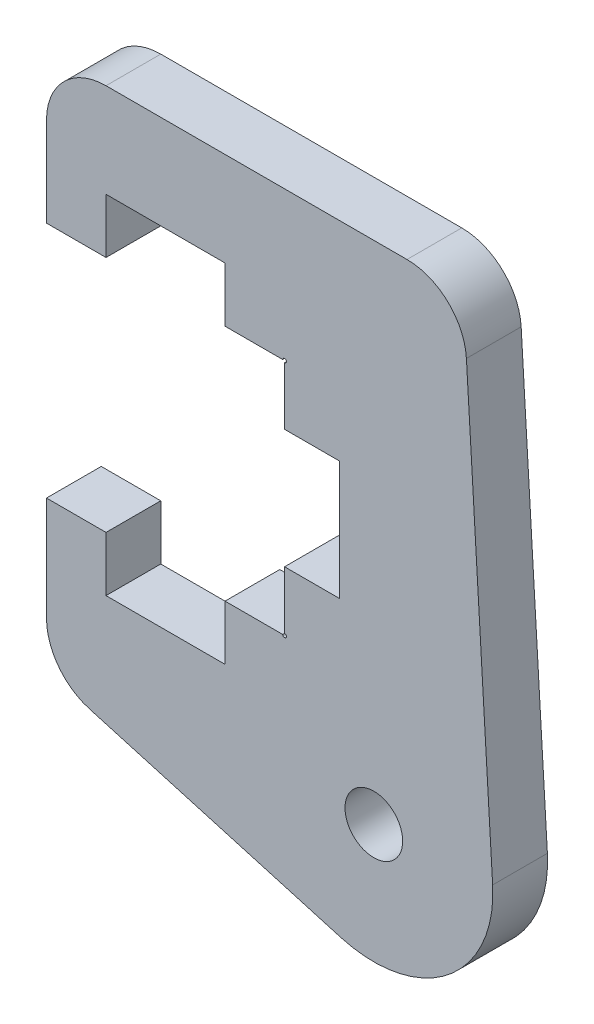
SolidWorks part; units mm, degrees
ref_plane "Front Plane" through (0, 0, 0) normal (0, 0, 1) x (1, 0, 0)
ref_plane "Top Plane" through (0, 0, 0) normal (0, 1, 0) x (1, 0, 0)
ref_plane "Right Plane" through (0, 0, 0) normal (1, 0, 0) x (0, 0, -1)
sketch "Sketch1" plane through (0, 0, 0) normal (0, 0, 1) x (1, 0, 0)
  line L0 (0, 12.7) -> (0, -12.7) construction
  line L1 (12.7, -12.7) -> (6.35, -12.7)
  line L2 (12.7, -12.7) -> (12.7, -6.35)
  line L3 (12.7, 12.7) -> (6.35, 12.7)
  line L4 (-12.7, 12.7) -> (-12.7, 28.575)
  line L5 (12.7, -12.7) -> (-12.7, 12.7) construction
  line L6 (12.7, 12.7) -> (-12.7, -12.7) construction
  line L7 (-12.7, 0) -> (12.7, 0) construction
  line L8 (12.7, 6.35) -> (12.7, 12.7)
  line L9 (18.542, -6.35) -> (12.7, -6.35)
  line L10 (18.542, -6.35) -> (18.542, 6.35)
  line L11 (18.542, 6.35) -> (12.7, 6.35)
  line L12 (-6.35, 12.7) -> (-12.7, 12.7)
  line L13 (18.542, -6.35) -> (12.7, 6.35) construction
  line L14 (18.542, 6.35) -> (12.7, -6.35) construction
  line L15 (6.35, 18.542) -> (-6.35, 18.542)
  line L16 (6.35, 18.542) -> (6.35, 12.7)
  line L17 (6.35, -18.542) -> (6.35, -12.7)
  line L18 (-6.35, 18.542) -> (-6.35, 12.7)
  line L19 (6.35, 18.542) -> (-6.35, 12.7) construction
  line L20 (6.35, 12.7) -> (-6.35, 18.542) construction
  line L21 (6.35, -18.542) -> (-6.35, -12.7) construction
  line L22 (6.35, -12.7) -> (-6.35, -18.542) construction
  line L23 (6.35, -18.542) -> (-6.35, -18.542)
  line L24 (-6.35, -18.542) -> (-6.35, -12.7)
  line L25 (-6.35, -12.7) -> (-12.7, -12.7)
  line L26 (-12.7, 28.575) -> (31.75, 28.575)
  line L27 (31.75, 28.575) -> (34.9028, -24.649)
  line L28 (-12.7, -12.7) -> (-12.7, -28.575)
  line L29 (-12.7, -28.575) -> (18.7164, -37.6057)
  circle A0 centre (22.225, -25.4) radius 3.075
  arc A1 (18.7164, -37.6057) -> (34.9028, -24.649) centre (22.225, -25.4) ccw
  point P0 (0, 0)
  point P10 (15.621, 0)
  point P15 (0, 15.621)
  dimension "D7" = 15.875
  dimension "D9" = 6.15
  dimension "D10" = 25.4
  dimension "D1" = 25.4
  dimension "D2" = 25.4
  dimension "D3" = 5.842
  dimension "D4" = 12.7
  dimension "D5" = 5.842
  dimension "D6" = 12.7
  dimension "D8" = 9.525
  dimension "D11" = 15.875
  dimension "D12" = 15.875
  dimension "D13" = 44.45
extrude "Boss-Extrude1" add sketch "Sketch1" along normal blind 5.842
fillet "Fillet1" radius 6.35 3 edges at (31.75, 28.575, 2.921) (-12.7, -28.575, 2.921) (-12.7, 28.575, 2.921)
sketch "Sketch2" plane through (0, 0, 5.842) normal (0, 0, 1) x (1, 0, 0)
  circle A0 centre (12.7, 12.7) radius 0.1984
  circle A1 centre (12.7, -12.7) radius 0.1984
  dimension "D1" = 0.3969
  dimension "D2" = 0.3969
extrude "Cut-Extrude1" cut sketch "Sketch2" against normal through all
